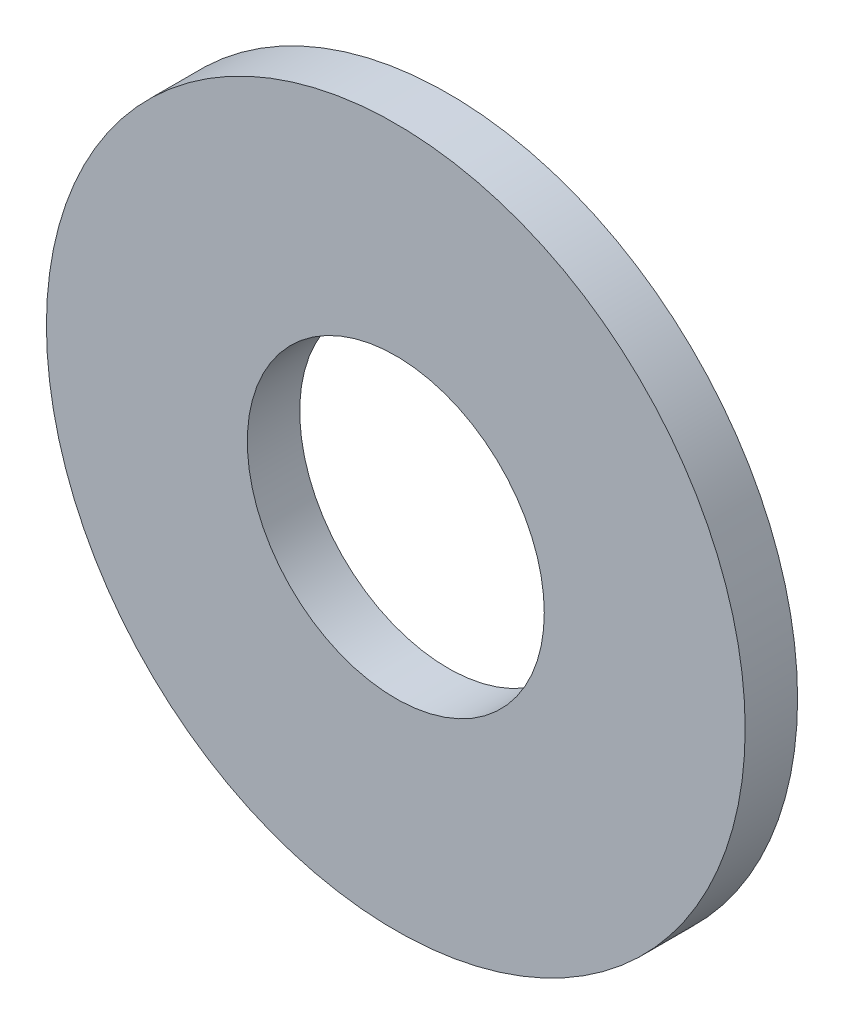
SolidWorks part; units mm, degrees
material "AISI 4340 Steel, normalized"
ref_plane "Front Plane" through (0, 0, 0) normal (0, 0, 1) x (1, 0, 0)
ref_plane "Top Plane" through (0, 0, 0) normal (0, 1, 0) x (1, 0, 0)
ref_plane "Right Plane" through (0, 0, 0) normal (1, 0, 0) x (0, 0, -1)
sketch "Sketch1" plane through (0, 0, 0) normal (0, 0, 1) x (1, 0, 0)
  circle A0 centre (0, 0) radius 2
  circle A1 centre (0, 0) radius 0.85
extrude "Washer" add sketch "Sketch1" along normal blind 0.3
